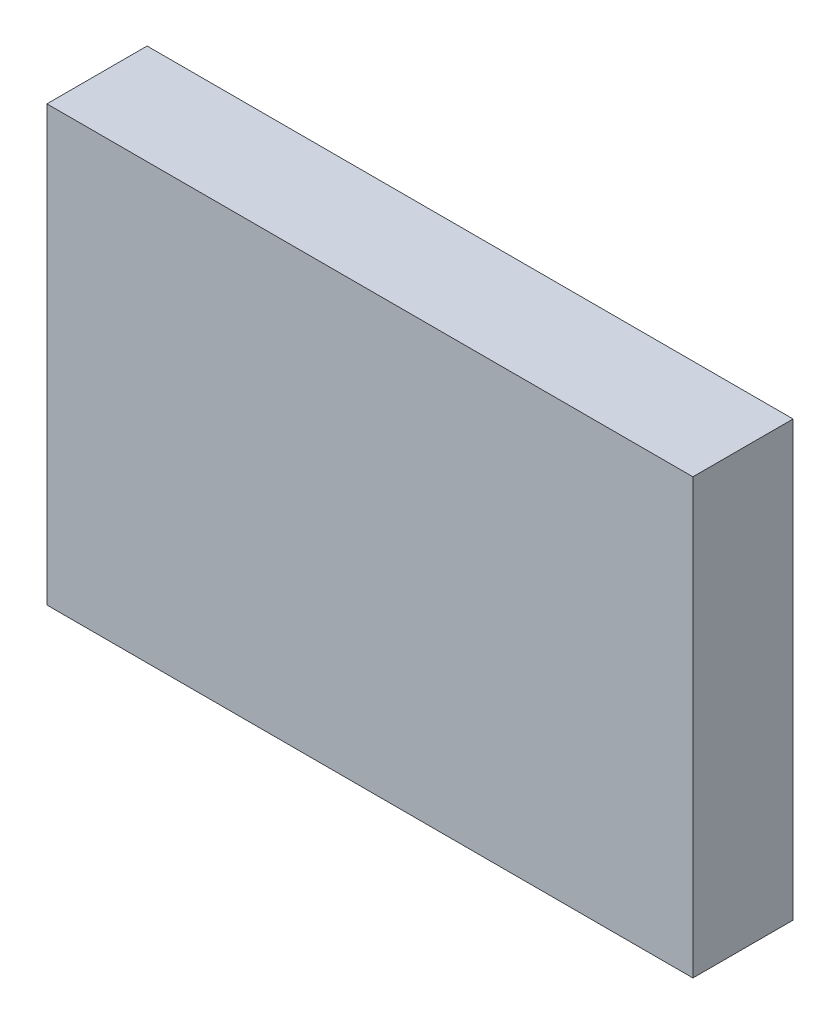
SolidWorks part; units mm, degrees
ref_plane "Plan de face" through (0, 0, 0) normal (0, 0, 1) x (1, 0, 0)
ref_plane "Plan de dessus" through (0, 0, 0) normal (0, 1, 0) x (1, 0, 0)
ref_plane "Plan de droite" through (0, 0, 0) normal (1, 0, 0) x (0, 0, -1)
sketch "Esquisse1" plane through (0, 0, 0) normal (0, 0, 1) x (1, 0, 0)
  line L0 (-0.0635, 56) -> (87, 56)
  line L1 (87, 56) -> (87, -2.5)
  line L2 (87, -2.5) -> (-0.0635, -2.5)
  line L3 (-0.0635, -2.5) -> (-0.0635, 56)
extrude "Component_Outline" add sketch "Esquisse1" along normal blind 13.5 separate body
sketch3d "Esquisse3D1"
  line L0 (0, 0, 0) -> (1, 0, 0)
  line L1 (0, 0, 0) -> (0, 1, 0)
  line L2 (0, 0, 0) -> (0, 0, 1)
  point P0 (0, 0, 0)
